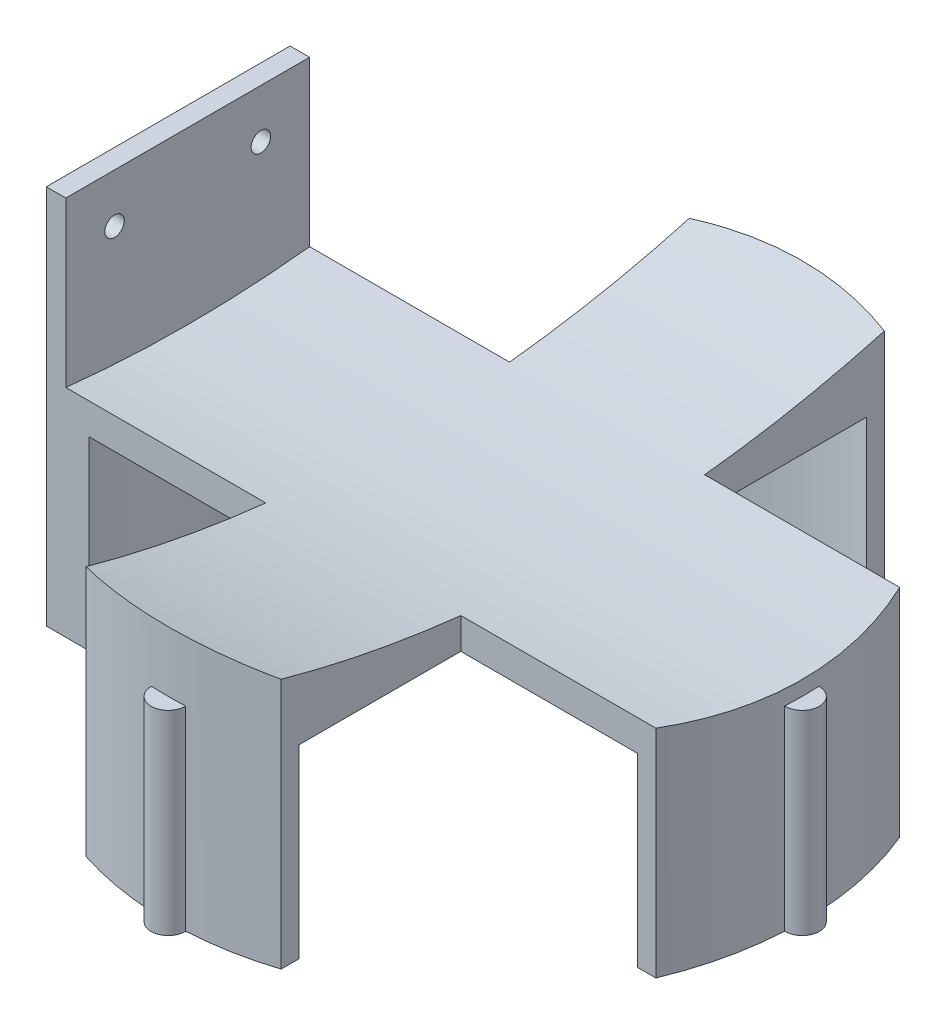
SolidWorks part; units mm, degrees
ref_plane "前视基准面" through (0, 0, 0) normal (0, 0, 1) x (1, 0, 0)
ref_plane "上视基准面" through (0, 0, 0) normal (0, 1, 0) x (1, 0, 0)
ref_plane "右视基准面" through (0, 0, 0) normal (1, 0, 0) x (0, 0, -1)
sketch "草图1" plane through (0, 0, 0) normal (1, 0, 0) x (0, 0, -1)
  line L1 (-25, 0) -> (25, 0)
  line L2 (-25, 0) -> (-25, -40)
  line L3 (-25, -40) -> (25, -40)
  line L4 (25, 0) -> (25, -40)
  dimension "D1" = 50
  dimension "D2" = 25
  dimension "D3" = 40
extrude "凸台-拉伸1" add sketch "草图1" along normal blind 4
sketch "草图2" plane through (4, 0, 0) normal (1, 0, 0) x (0, 0, -1)
  line L1 (-15, -10) -> (15, -10) construction
  line L2 (25, 0) -> (-25, 0) construction
  circle A0 centre (-15, -10) radius 2
  circle A1 centre (15, -10) radius 2
  dimension "D4" = 4
  dimension "D5" = 4
  dimension "D1" = 30
  dimension "D2" = 10
  dimension "D3" = 15
extrude "切除-拉伸1" cut sketch "草图2" against normal blind 4
sketch "草图3" plane through (4, 0, 0) normal (1, 0, 0) x (0, 0, -1)
  line L0 (-25, -40) -> (25, -40) construction
  line L1 (-25, -33.6373) -> (-25, -38.6664)
  line L2 (-25, 0) -> (-25, -40) construction
  line L6 (25, -40) -> (25, 0) construction
  line L7 (25, -38.6664) -> (25, -33.6373)
  arc A0 (-25, -33.6373) -> (25, -33.6373) centre (0, 195) ccw
  arc A1 (-25, -38.6664) -> (25, -38.6664) centre (0, 195) ccw
  dimension "D1" = 460
  dimension "D2" = 470
extrude "凸台-拉伸2" add sketch "草图3" along normal blind 180
sketch "草图4" plane through (4, 0, 0) normal (1, 0, 0) x (0, 0, -1)
  line L2 (0, -40) -> (25, -40)
  line L3 (25, -40) -> (25, -38.6664)
  line L4 (0, -40) -> (25, -40)
  line L5 (25, -40) -> (25, -38.6664)
  line L6 (-25, -38.6664) -> (-25, -40)
  line L7 (-25, -40) -> (0, -40)
  line L8 (-25, -38.6664) -> (-25, -40)
  line L9 (-25, -40) -> (0, -40)
  arc A1 (0, -40) -> (25, -38.6664) centre (0, 195) ccw
  arc A2 (0, -40) -> (25, -38.6664) centre (0, 195) ccw
  arc A3 (-25, -38.6664) -> (0, -40) centre (0, 195) ccw
  arc A4 (-25, -38.6664) -> (0, -40) centre (0, 195) ccw
  arc M7 (25, -38.6664) -> (0, -40) centre (0, 195) cw
  line M8 (0, -40) -> (25, -40)
  line M9 (25, -40) -> (25, -38.6664)
  dimension "D1" = 0
  dimension "D2" = 0
extrude "切除-拉伸2" cut sketch "草图4" against normal blind 60 contours M9 M7 M8
sketch "草图5" plane through (4, 0, 0) normal (1, 0, 0) x (0, 0, -1)
  line L2 (-25, -38.6664) -> (-25, -40)
  line L3 (-25, -40) -> (0, -40)
  line L4 (-25, -38.6664) -> (-25, -40)
  line L5 (-25, -40) -> (0, -40)
  arc A1 (-25, -38.6664) -> (0, -40) centre (0, 195) ccw
  arc A2 (-25, -38.6664) -> (0, -40) centre (0, 195) ccw
  dimension "D1" = 0
extrude "切除-拉伸3" cut sketch "草图5" against normal blind 60
ref_plane "基准面1" through (0, -40, 0) normal (0, -1, 0) x (-1, 0, 0)
sketch "草图6" plane through (0, -40, 0) normal (0, -1, 0) x (-1, 0, 0)
  line L2 (-85.0023, 61.8458) -> (-85.0023, 25)
  line L4 (-45.0023, 61.8473) -> (-45.0023, 25)
  line L5 (-125, 25) -> (-85.0023, 25)
  line L7 (-125, -25) -> (-85.0023, -25)
  line L9 (-85.0023, -25) -> (-85.0023, -61.8458)
  line L10 (-45.0023, -25) -> (-45.0023, -61.8473)
  line L11 (-45.0023, 25) -> (-5, 25)
  line L12 (-45.0023, -25) -> (-5, -25)
  arc A0 (-5, -25) -> (-5, 25) centre (-65, 0) ccw
  arc A1 (-85.0023, -61.8458) -> (-45.0023, -61.8473) centre (-65, 0) ccw
  arc A2 (-125, 25) -> (-125, -25) centre (-65, 0) ccw
  arc A3 (-45.0023, 61.8473) -> (-85.0023, 61.8458) centre (-65, 0) ccw
  dimension "D1" = 130
  dimension "D2" = 50
  dimension "D3" = 40
  dimension "D4" = 25
  dimension "D5" = 65
  dimension "D7" = 45.0023
extrude "凸台-拉伸3" add sketch "草图6" against normal up to surface (6.3627 mm away)
mirror "镜向1" about plane through (0, 0, 0) normal (0, 0, 1) of "凸台-拉伸3"
sketch "草图7" plane through (0, -40, 0) normal (0, -1, 0) x (1, 0, 0)
  line L8 (5, -25) -> (45.0023, -25)
  line L9 (45.0023, -25) -> (45.0023, -61.8473)
  line L10 (85.0023, -61.8458) -> (85.0023, -25)
  line L11 (85.0023, -25) -> (125, -25)
  line L12 (125, 25) -> (85.0023, 25)
  line L13 (85.0023, 25) -> (85.0023, 61.8458)
  line L14 (45.0023, 61.8473) -> (45.0023, 25)
  line L15 (45.0023, 25) -> (5, 25)
  line L16 (5, -25) -> (8.8106, -25)
  line L17 (45.0023, -58.1579) -> (45.0023, -61.8473)
  line L18 (85.0023, -61.8458) -> (85.0023, -58.1563)
  line L19 (121.1894, -25) -> (125, -25)
  line L20 (125, 25) -> (121.1894, 25)
  line L21 (85.0023, 58.1563) -> (85.0023, 61.8458)
  line L22 (45.0023, 61.8473) -> (45.0023, 58.1579)
  line L23 (8.8106, 25) -> (5, 25)
  arc A0 (8.8106, 25) -> (8.8106, -25) centre (65, 0) ccw
  arc A1 (85.0023, 58.1563) -> (45.0023, 58.1579) centre (65, 0) ccw
  arc A2 (121.1894, -25) -> (121.1894, 25) centre (65, 0) ccw
  arc A3 (45.0023, -58.1579) -> (85.0023, -58.1563) centre (65, 0) ccw
  arc A7 (5, 25) -> (0, 0) centre (65, 0) ccw
  arc A8 (0, 0) -> (5, -25) centre (65, 0) ccw
  arc A9 (45.0023, -61.8473) -> (85.0023, -61.8458) centre (65, 0) ccw
  arc A10 (125, -25) -> (130, 0) centre (65, 0) ccw
  arc A11 (130, 0) -> (125, 25) centre (65, 0) ccw
  arc A12 (85.0023, 61.8458) -> (45.0023, 61.8473) centre (65, 0) ccw
  arc A13 (5, 25) -> (0, 0) centre (65, 0) ccw
  arc A14 (0, 0) -> (5, -25) centre (65, 0) ccw
  arc A15 (45.0023, -61.8473) -> (85.0023, -61.8458) centre (65, 0) ccw
  arc A16 (125, -25) -> (130, 0) centre (65, 0) ccw
  arc A17 (130, 0) -> (125, 25) centre (65, 0) ccw
  arc A18 (85.0023, 61.8458) -> (45.0023, 61.8473) centre (65, 0) ccw
  dimension "D1" = 123
  dimension "D2" = 65
  dimension "D3" = 0
extrude "凸台-拉伸4" add sketch "草图7" along normal blind 38
sketch "草图8" plane through (0, -78, 0) normal (0, -1, 0) x (1, 0, 0)
  line L3 (184, 25) -> (125, 25)
  line L4 (125, -25) -> (184, -25)
  line L5 (184, -25) -> (184, 25)
  line L6 (184, 25) -> (125, 25)
  line L7 (125, -25) -> (184, -25)
  line L8 (184, -25) -> (184, 25)
  arc A1 (125, -25) -> (125, 25) centre (65, 0) ccw
  arc A2 (125, -25) -> (125, 25) centre (65, 0) ccw
  dimension "D1" = 0
extrude "切除-拉伸4" cut sketch "草图8" against normal through all
sketch "草图9" plane through (0, -78, 0) normal (0, -1, 0) x (1, 0, 0)
  circle A0 centre (130, 0) radius 3.5
  arc A1 (125, -25) -> (125, 25) centre (65, 0) ccw construction
  circle A2 centre (65.0025, -65) radius 3.5
  arc A3 (45.0023, -61.8473) -> (85.0023, -61.8458) centre (65, 0) ccw construction
  circle A4 centre (65.0025, 65) radius 3.5
  arc A5 (85.0023, 61.8458) -> (45.0023, 61.8473) centre (65, 0) ccw construction
  dimension "D1" = 7
  dimension "D2" = 7
  dimension "D3" = 7
extrude "凸台-拉伸5" add sketch "草图9" against normal blind 40
sketch "草图10" plane through (0, -78, 0) normal (0, -1, 0) x (1, 0, 0)
  circle A0 centre (65.0025, 65) radius 1.5
  circle A1 centre (130, 0) radius 1.5
  circle A2 centre (65.0025, -65) radius 1.5
  dimension "D1" = 3
  dimension "D2" = 3
  dimension "D3" = 3
extrude "切除-拉伸5" cut sketch "草图10" against normal blind 30
chamfer "倒角1" distance 0.5 angle 45 3 edges at (65.0025, -78, 63.5) (130, -78, -1.5) (65.0025, -78, -66.5)
sketch "草图11" plane through (0, -78, 0) normal (0, -1, 0) x (1, 0, 0)
  line L2 (0, 25) -> (0, 0)
  line L3 (5, 25) -> (0, 25)
  line L4 (0, 25) -> (0, 0)
  line L5 (5, 25) -> (0, 25)
  arc A1 (5, 25) -> (0, 0) centre (65, 0) ccw
  arc A2 (5, 25) -> (0, 0) centre (65, 0) ccw
  dimension "D1" = 0
extrude "凸台-拉伸6" add sketch "草图11" against normal up to next
sketch "草图12" plane through (0, -78, 0) normal (0, -1, 0) x (1, 0, 0)
  line L2 (0, -25) -> (5, -25)
  line L3 (0, 0) -> (0, -25)
  line L4 (0, -25) -> (5, -25)
  line L5 (0, 0) -> (0, -25)
  arc A1 (0, 0) -> (5, -25) centre (65, 0) ccw
  arc A2 (0, 0) -> (5, -25) centre (65, 0) ccw
  dimension "D1" = 0
extrude "凸台-拉伸7" add sketch "草图12" against normal up to next
